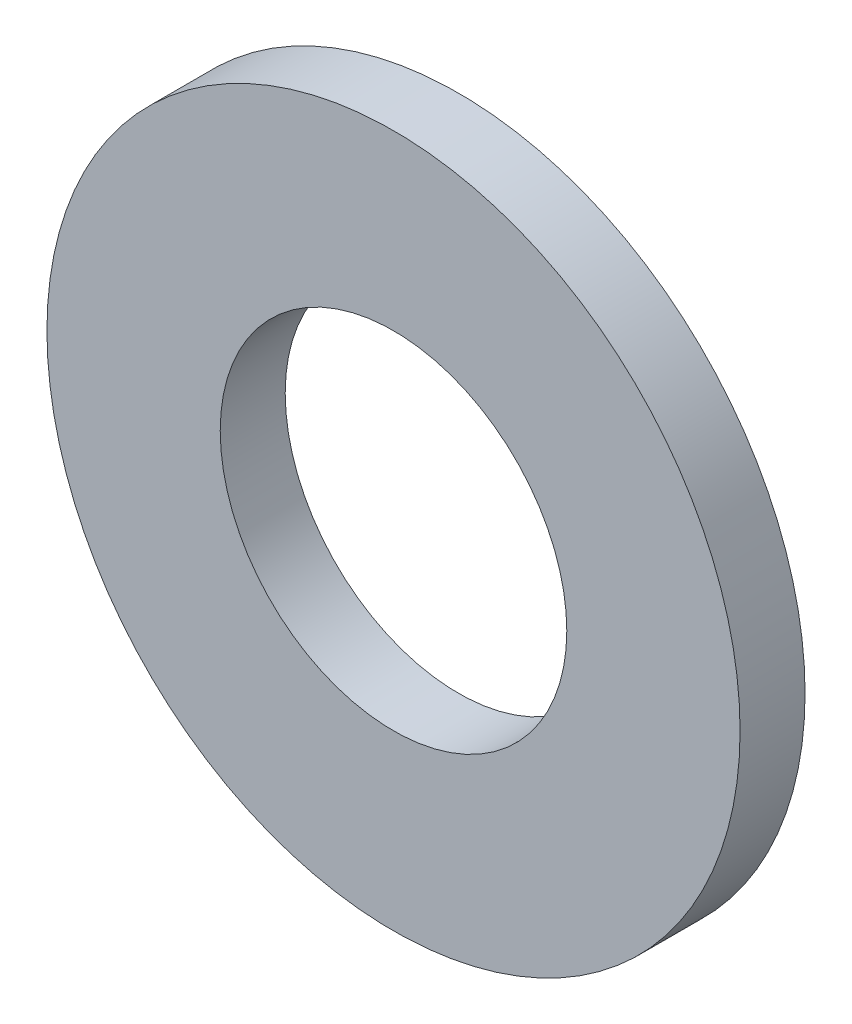
SolidWorks part; units mm, degrees
ref_plane "Plan1" through (0, 0, 0) normal (0, 0, 1) x (1, 0, 0)
ref_plane "Plan2" through (0, 0, 0) normal (0, 1, 0) x (1, 0, 0)
ref_plane "Plan3" through (0, 0, 0) normal (1, 0, 0) x (0, 0, -1)
sketch "Esquisse1" plane through (0, 0, 0) normal (0, 0, 1) x (1, 0, 0)
  circle A0 centre (0, 0) radius 4
  circle A1 centre (0, 0) radius 8
  dimension "D1" = 8
  dimension "D2" = 16
extrude "Base-Extrusion" add sketch "Esquisse1" along normal blind 1.5
